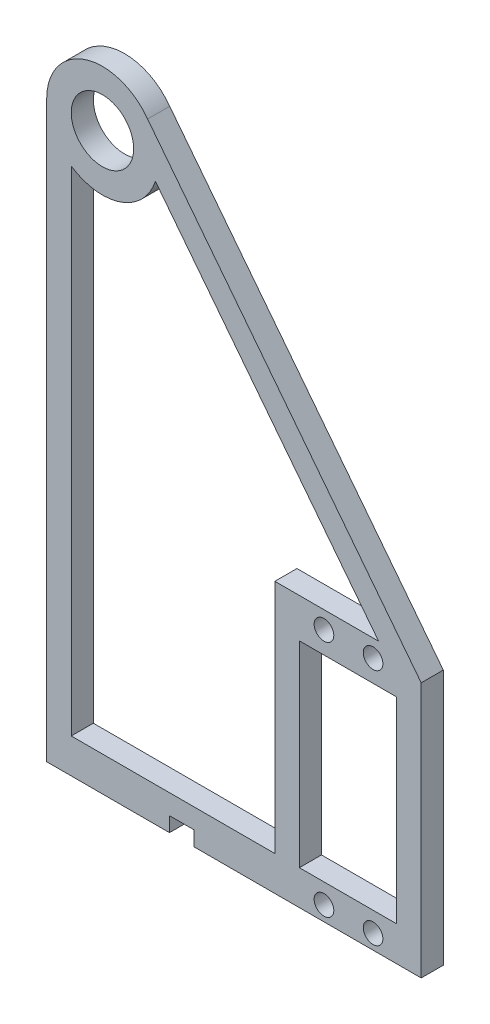
SolidWorks part; units mm, degrees
material "Acrylic (Medium-high impact)"
ref_plane "Front Plane" through (0, 0, 0) normal (0, 0, 1) x (1, 0, 0)
ref_plane "Top Plane" through (0, 0, 0) normal (0, 1, 0) x (1, 0, 0)
ref_plane "Right Plane" through (0, 0, 0) normal (1, 0, 0) x (0, 0, -1)
sketch "Sketch1" plane through (0, 0, 0) normal (0, 0, 1) x (1, 0, 0)
  line L0 (0, 0) -> (50, -100) construction
  line L1 (50, -100) -> (50, -89.9) construction
  line L3 (59.9, -69.9) -> (40.1, -69.9)
  line L4 (59.9, -69.9) -> (59.9, -109.9)
  line L5 (59.9, -109.9) -> (40.1, -109.9)
  line L6 (40.1, -69.9) -> (40.1, -109.9)
  line L7 (59.9, -69.9) -> (40.1, -109.9) construction
  line L8 (59.9, -109.9) -> (40.1, -69.9) construction
  line L9 (35.1, -64.9) -> (35.1, -109.9)
  line L11 (64.9, -64.9) -> (64.9, -114.9)
  line L12 (64.9, -64.9) -> (9.1971, 6.651)
  line L13 (-11.35, 0) -> (-11.35, -114.9)
  line L15 (56.2279, -61.9) -> (10.7869, -3.5305)
  line L16 (-6.35, -9.4074) -> (-6.35, -109.9)
  line L17 (-6.35, -109.9) -> (35.1, -109.9)
  line L18 (-11.35, -116.95) -> (35.1, -116.95)
  line L19 (60.9546, -67.9715) -> (5.2517, 3.5795) construction
  line L20 (-6.35, 0) -> (-6.35, -109.9) construction
  line L21 (64.9, -64.9) -> (35.1, -64.9) construction
  line L22 (35.1, -64.9) -> (35.1, -114.9) construction
  line L23 (64.9, -116.95) -> (35.1, -116.95)
  line L24 (-11.35, -114.9) -> (-11.35, -116.95)
  line L25 (64.9, -116.95) -> (64.9, -114.9)
  line L26 (56.2279, -61.9) -> (35.1, -61.9)
  line L27 (-11.35, -114.9) -> (35.1, -114.9) construction
  line L28 (64.9, -114.9) -> (35.1, -114.9) construction
  line L29 (35.1, -64.9) -> (35.1, -61.9)
  circle A0 centre (0, 0) radius 6.35
  circle A1 centre (50, -100) radius 9.9
  arc A2 (-6.35, -9.4074) -> (10.7869, -3.5305) centre (0, 0) ccw
  arc A3 (9.1971, 6.651) -> (-11.35, 0) centre (0, 0) ccw
  circle A4 centre (0, 0) radius 11.35 construction
  point P27 (11.35, 0)
  point P31 (58.5635, -61.9)
  dimension "D1" = 12.7
  dimension "D4" = 19.8
  dimension "D2" = 50
  dimension "D3" = 100
  dimension "D5" = 10.1
  dimension "D6" = 5
  dimension "D7" = 5
  dimension "D8" = 5
  dimension "D9" = 5
extrude "Boss-Extrude1" add sketch "Sketch1" along normal blind 4.5
sketch "Sketch2" plane through (0, 0, 0) normal (0, 0, -1) x (-1, 0, 0)
  circle A0 centre (-55.1, -113.95) radius 2
  circle A1 centre (-45.1, -113.95) radius 2
  circle A2 centre (-45.1, -65.45) radius 2
  circle A3 centre (-55.1, -65.45) radius 2
extrude "Cut-Extrude1" cut sketch "Sketch2" against normal through all
sketch "Sketch3" plane through (0, 0, 4.5) normal (0, 0, 1) x (1, 0, 0)
  line L0 (-11.35, -116.95) -> (64.9, -116.95) construction
  line L1 (13.65, -116.95) -> (18.65, -116.95)
  line L2 (13.65, -116.95) -> (13.65, -113.95)
  line L3 (13.65, -113.95) -> (18.65, -113.95)
  line L4 (18.65, -116.95) -> (18.65, -113.95)
  line L5 (-11.35, 0) -> (-11.35, -116.95) construction
  dimension "D1" = 5
  dimension "D2" = 3
  dimension "D3" = 25
extrude "Cut-Extrude2" cut sketch "Sketch3" against normal through all
equation "\"w\" = 50"
equation "\"D2@Sketch1\"=\"w\""
equation "\"H\"= 130"
